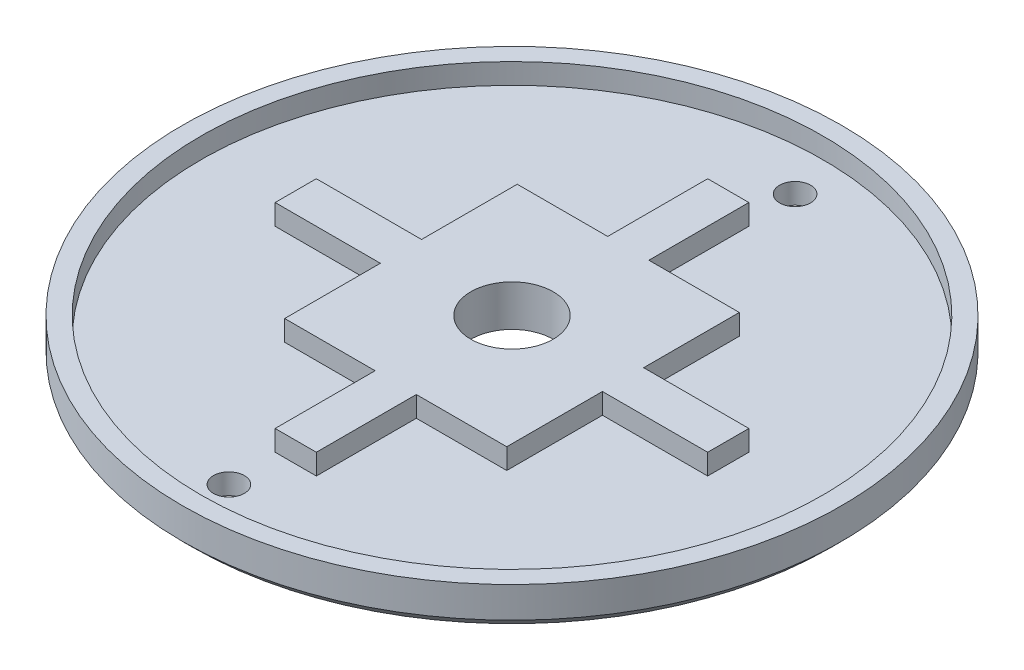
SolidWorks part; units mm, degrees
ref_plane "Front Plane" through (0, 0, 0) normal (0, 0, 1) x (1, 0, 0)
ref_plane "Top Plane" through (0, 0, 0) normal (0, 1, 0) x (1, 0, 0)
ref_plane "Right Plane" through (0, 0, 0) normal (1, 0, 0) x (0, 0, -1)
sketch "Sketch1" plane through (0, 0, 0) normal (0, 1, 0) x (1, 0, 0)
  circle A0 centre (0, 0) radius 32
  dimension "D1" = 64
extrude "Boss-Extrude1" add sketch "Sketch1" along normal blind 4
sketch "Sketch2" plane through (0, 4, 0) normal (0, 1, 0) x (1, 0, 0)
  circle A2 centre (0, 0) radius 30.2
  circle A3 centre (0, 0) radius 30.2
  dimension "D1" = 1.8
extrude "Cut-Extrude1" cut sketch "Sketch2" against normal blind 2
chamfer "Chamfer1" distance 1 angle 45 1 edges at (0, 0, 32)
sketch "Sketch3" plane through (0, 0, 0) normal (0, -1, 0) x (1, 0, 0)
  circle A0 centre (-1.532, 25.9548) radius 1.5
  circle A1 centre (1.532, -25.9548) radius 1.5
  dimension "D1" = 3
extrude "Cut-Extrude2" cut sketch "Sketch3" against normal blind 15
sketch "Sketch5" plane through (0, 2, 0) normal (0, 1, 0) x (1, 0, 0)
  line L0 (0, 21) -> (0, -21) construction
  line L1 (-21, 0) -> (21, 0) construction
  line L2 (-2, 21) -> (-2, -21)
  line L3 (-21, -2) -> (21, -2)
  line L4 (2, 21) -> (2, -21)
  line L5 (-21, 2) -> (21, 2)
  line L6 (-2, 21) -> (2, 21)
  line L7 (-2, -21) -> (2, -21)
  line L8 (-21, -2) -> (-21, 2)
  line L9 (21, -2) -> (21, 2)
  dimension "D1" = 2
  dimension "D2" = 2
extrude "Boss-Extrude2" add sketch "Sketch5" along normal blind 2 contours L5 L9 L3 L8 | L2 L7 L4 L6
sketch "Sketch6" plane through (0, 4, 0) normal (0, 1, 0) x (1, 0, 0)
  circle A0 centre (0, 0) radius 4
  dimension "D1" = 8
extrude "Cut-Extrude3" cut sketch "Sketch6" against normal blind 10
sketch "Sketch7" plane through (0, 2, 0) normal (0, 1, 0) x (1, 0, 0)
  line L1 (-7.5, -10) -> (7.5, -10)
  line L2 (-7.5, -10) -> (-7.5, 10)
  line L3 (-7.5, 10) -> (7.5, 10)
  line L4 (7.5, -10) -> (7.5, 10)
  line L5 (-7.5, -10) -> (7.5, 10) construction
  line L6 (-7.5, 10) -> (7.5, -10) construction
  point P0 (0, 0)
  dimension "D1" = 15
extrude "Cut-Extrude4" cut sketch "Sketch7" along normal blind 10
sketch "Sketch8" plane through (0, 2, 0) normal (0, 1, 0) x (1, 0, 0)
  line L1 (-10.7821, -11.2912) -> (10.7821, -11.2912)
  line L2 (-10.7821, -11.2912) -> (-10.7821, 11.2912)
  line L3 (-10.7821, 11.2912) -> (10.7821, 11.2912)
  line L4 (10.7821, -11.2912) -> (10.7821, 11.2912)
  line L5 (-10.7821, -11.2912) -> (10.7821, 11.2912) construction
  line L6 (-10.7821, 11.2912) -> (10.7821, -11.2912) construction
  circle A0 centre (0, 0) radius 4
  point P0 (0, 0)
extrude "Boss-Extrude3" add sketch "Sketch8" along normal blind 2
